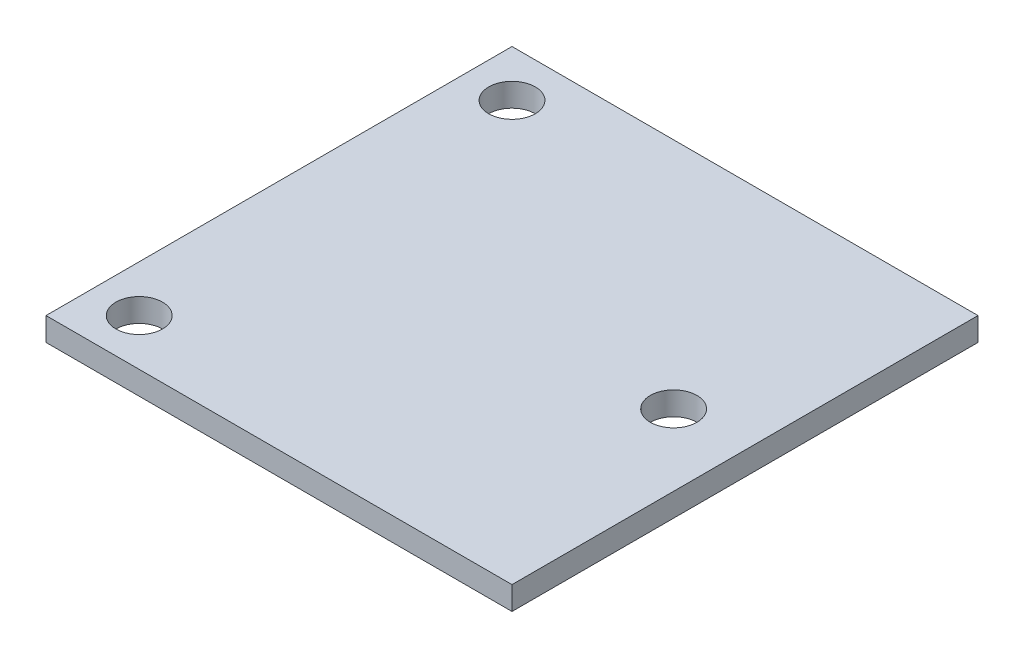
SolidWorks part; units mm, degrees
material "Cast Alloy Steel"
ref_plane "Front Plane" through (0, 0, 0) normal (0, 0, 1) x (1, 0, 0)
ref_plane "Top Plane" through (0, 0, 0) normal (0, 1, 0) x (1, 0, 0)
ref_plane "Right Plane" through (0, 0, 0) normal (1, 0, 0) x (0, 0, -1)
sketch "Sketch1" plane through (0, 0, 0) normal (0, 1, 0) x (1, 0, 0)
  line L0 (12.7, 50.8) -> (12.7, -50.8) construction
  line L1 (0, -63.5) -> (127, -63.5)
  line L2 (0, -63.5) -> (0, 63.5)
  line L3 (0, 63.5) -> (127, 63.5)
  line L4 (127, -63.5) -> (127, 63.5)
  line L5 (0, 63.5) -> (12.7, 50.8) construction
  line L6 (0, -63.5) -> (12.7, -50.8) construction
  line L7 (12.7, -50.8) -> (107.5507, 0) construction
  line L8 (107.5507, 0) -> (12.7, 50.8) construction
  circle A0 centre (12.7, 50.8) radius 6.35
  circle A1 centre (12.7, -50.8) radius 6.35
  circle A2 centre (107.5507, 0) radius 6.35
  point P0 (0, 0)
  point P13 (0, 0)
  point P15 (0, 0)
  dimension "D2" = 12.7
  dimension "D3" = 12.7
  dimension "D4" = 101.6
  dimension "D1" = 12.7
  dimension "D6" = 45
  dimension "D7" = 45
  dimension "D5" = 127
  dimension "D8" = 107.5507
extrude "Boss-Extrude1" add sketch "Sketch1" along normal blind 6.35
